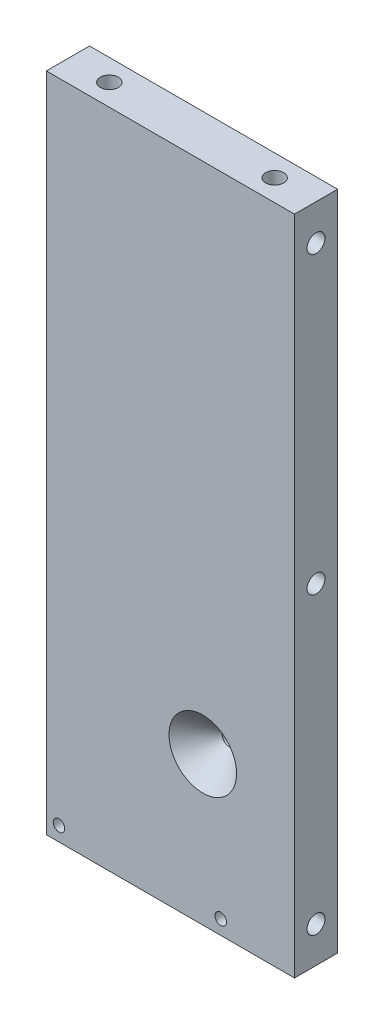
SolidWorks part; units mm, degrees
material "POM Ацеталь кополимер"
ref_plane "Front" through (0, 0, 0) normal (0, 0, 1) x (1, 0, 0)
ref_plane "Top" through (0, 0, 0) normal (0, 1, 0) x (1, 0, 0)
ref_plane "Right" through (0, 0, 0) normal (1, 0, 0) x (0, 0, -1)
sketch "Эскиз1" plane through (0, 0, 0) normal (0, 0, 1) x (1, 0, 0)
  line L1 (-17.25, 46) -> (17.25, 46)
  line L2 (-17.25, 46) -> (-17.25, -46)
  line L3 (-17.25, -46) -> (17.25, -46)
  line L4 (17.25, 46) -> (17.25, -46)
  line L5 (-17.25, 46) -> (17.25, -46) construction
  line L6 (-17.25, -46) -> (17.25, 46) construction
  point P0 (0, 0)
  dimension "D1" = 92
  dimension "D2" = 34.5
extrude "База" add sketch "Эскиз1" along normal blind 6
hole_wizard "Сторона-1-M3" positions "Эскиз4" profile "Эскиз5" tap size "M3" standard "ISO"
sketch "Эскиз4" plane through (17.25, 0, 0) normal (1, 0, 0) x (0, 0, -1)
  line L0 (-3, 0) -> (0, 0) construction
  line L1 (0, -46) -> (0, 46) construction
  line L4 (-3, 0) -> (-6, 0) construction
  line L5 (-6, -46) -> (-6, 46) construction
  line L8 (-3, 0) -> (-3, 41) construction
  line L11 (-3, 0) -> (-3, -41) construction
  point P0 (-3, 41)
  point P2 (-3, 0)
  point P4 (-3, -41)
  dimension "D1" = 82
cosmetic thread "Отверстие резьбы1" parameters "D1"=5.5, "D2"=3
cosmetic thread "Отверстие резьбы2" parameters "D1"=5.5, "D2"=3
cosmetic thread "Отверстие резьбы3" parameters "D1"=5.5, "D2"=3
sketch "Эскиз5" plane through (17.25, 41, 3) normal (0, 1, 0) x (0, 0, -1)
  line L0 (0, 0) -> (0, 6.7511)
  line L1 (0, 6.7511) -> (1.25, 6)
  line L2 (1.25, 6) -> (1.25, 0)
  line L5 (1.25, 0) -> (0, 0)
  line L10 (0, 6.7511) -> (-1.25, 6) construction
  line L11 (0, -6.35) -> (0, 107.95) construction
  dimension "Диаметр сверла" = 2.5
  dimension "Глубина сверла" = 6
  dimension "Угол заточки сверла" = 118
hole_wizard "Сторона-2-M3" positions "Эскиз18" profile "Эскиз19" tap size "M3" standard "ISO"
sketch "Эскиз18" plane through (-17.25, 0, 0) normal (-1, 0, 0) x (0, 0, 1)
  point P0 (3, 0)
  point P3 (3, 41)
  point P6 (3, -41)
sketch "Эскиз19" plane through (-17.25, 0, 3) normal (0, 1, 0) x (0, 0, 1)
  line L0 (0, 0) -> (0, 6.7511)
  line L1 (0, 6.7511) -> (1.25, 6)
  line L2 (1.25, 6) -> (1.25, 0)
  line L5 (1.25, 0) -> (0, 0)
  line L10 (0, 6.7511) -> (-1.25, 6) construction
  line L11 (0, -6.35) -> (0, 107.95) construction
  dimension "Диаметр сверла" = 2.5
  dimension "Глубина сверла" = 6
  dimension "Угол заточки сверла" = 118
cosmetic thread "Отверстие резьбы13" parameters "D1"=5.5, "D2"=3
cosmetic thread "Отверстие резьбы14" parameters "D1"=5.5, "D2"=3
cosmetic thread "Отверстие резьбы15" parameters "D1"=5.5, "D2"=3
hole_wizard "Низ-M3" positions "Эскиз6" profile "Эскиз7" tap size "M3" standard "ISO"
sketch "Эскиз6" plane through (0, -46, 0) normal (0, -1, 0) x (-1, 0, 0)
  line L0 (11.5, -3) -> (0, -3) construction
  line L1 (0, -3) -> (-11.5, -3) construction
  line L4 (-17.25, -6) -> (-17.25, 0) construction
  point P0 (11.5, -3)
  point P2 (-11.5, -3)
  point P13 (-17.25, -3)
  dimension "D1" = 23
cosmetic thread "Отверстие резьбы4" parameters "D1"=5.5, "D2"=3
cosmetic thread "Отверстие резьбы5" parameters "D1"=5.5, "D2"=3
sketch "Эскиз7" plane through (-11.5, -46, 3) normal (1, 0, 0) x (0, 0, -1)
  line L0 (0, 0) -> (0, 6.7511)
  line L1 (0, 6.7511) -> (1.25, 6)
  line L2 (1.25, 6) -> (1.25, 0)
  line L5 (1.25, 0) -> (0, 0)
  line L10 (0, 6.7511) -> (-1.25, 6) construction
  line L11 (0, -6.35) -> (0, 107.95) construction
  dimension "Диаметр сверла" = 2.5
  dimension "Глубина сверла" = 6
  dimension "Угол заточки сверла" = 118
hole_wizard "Верх-M3" positions "Эскиз16" profile "Эскиз17" tap size "M3" standard "ISO"
sketch "Эскиз16" plane through (0, 46, 0) normal (0, 1, 0) x (1, 0, 0)
  point P0 (-11.5, -3)
  point P3 (11.5, -3)
sketch "Эскиз17" plane through (-11.5, 46, 3) normal (1, 0, 0) x (0, 0, 1)
  line L0 (0, 0) -> (0, 6.7511)
  line L1 (0, 6.7511) -> (1.25, 6)
  line L2 (1.25, 6) -> (1.25, 0)
  line L5 (1.25, 0) -> (0, 0)
  line L10 (0, 6.7511) -> (-1.25, 6) construction
  line L11 (0, -6.35) -> (0, 107.95) construction
  dimension "Диаметр сверла" = 2.5
  dimension "Глубина сверла" = 6
  dimension "Угол заточки сверла" = 118
cosmetic thread "Отверстие резьбы11" parameters "D1"=5.5, "D2"=3
cosmetic thread "Отверстие резьбы12" parameters "D1"=5.5, "D2"=3
hole_wizard "Натяжение-M4" positions "Эскиз8" profile "Эскиз9" countersink size "M4" standard "DIN" end condition through all
sketch "Эскиз8" plane through (0, 0, 6) normal (0, 0, 1) x (1, 0, 0)
  line L4 (17.25, -46) -> (17.25, 46) construction
  line L5 (-17.25, -46) -> (17.25, -46) construction
  point P14 (4.5, -25.4)
  dimension "D1" = 12.75
  dimension "D2" = 20.6
sketch "Эскиз9" plane through (4.5, -25.4, 6) normal (1, 0, 0) x (0, -1, 0)
  line L0 (0, 0) -> (0, 6)
  line L1 (0, 6) -> (1, 6)
  line L2 (1, 6) -> (1, 3.7)
  line L3 (1, 3.7) -> (4.7, 0)
  line L5 (4.7, 0) -> (0, 0)
  line L6 (-1, 3.7) -> (-4.7, 0) construction
  line L11 (0, -6.35) -> (0, 107.95) construction
  dimension "Диаметр сквозного отверстия" = 2
  dimension "Глубина сквозного отверстия" = 6
  dimension "Диаметр передней зенковки" = 9.4
  dimension "Угол передней зенковки" = 90
hole_wizard "Отверстие обработанное метчиком M21" positions "Эскиз12" profile "Эскиз13" tap size "M2" standard "DIN" end condition through all
sketch "Эскиз12" plane through (0, 0, 6) normal (0, 0, 1) x (1, 0, 0)
  line L0 (-17.25, 46) -> (-17.25, -46) construction
  line L1 (-17.25, -46) -> (17.25, -46) construction
  point P0 (-15.5, -44)
  point P3 (7, -44)
  dimension "D1" = 22.5
  dimension "D2" = 1.75
  dimension "D3" = 2
sketch "Эскиз13" plane through (-15.5, -44, 6) normal (1, 0, 0) x (0, -1, 0)
  line L0 (0, 0) -> (0, 6)
  line L1 (0, 6) -> (0.8, 6)
  line L2 (0.8, 6) -> (0.8, 0)
  line L5 (0.8, 0) -> (0, 0)
  line L11 (0, -6.35) -> (0, 107.95) construction
  dimension "Диаметр проходного сверла" = 1.6
  dimension "Глубина проходного сверла" = 6
cosmetic thread "Отверстие резьбы8" parameters "D2"=2
cosmetic thread "Отверстие резьбы9" parameters "D2"=2
